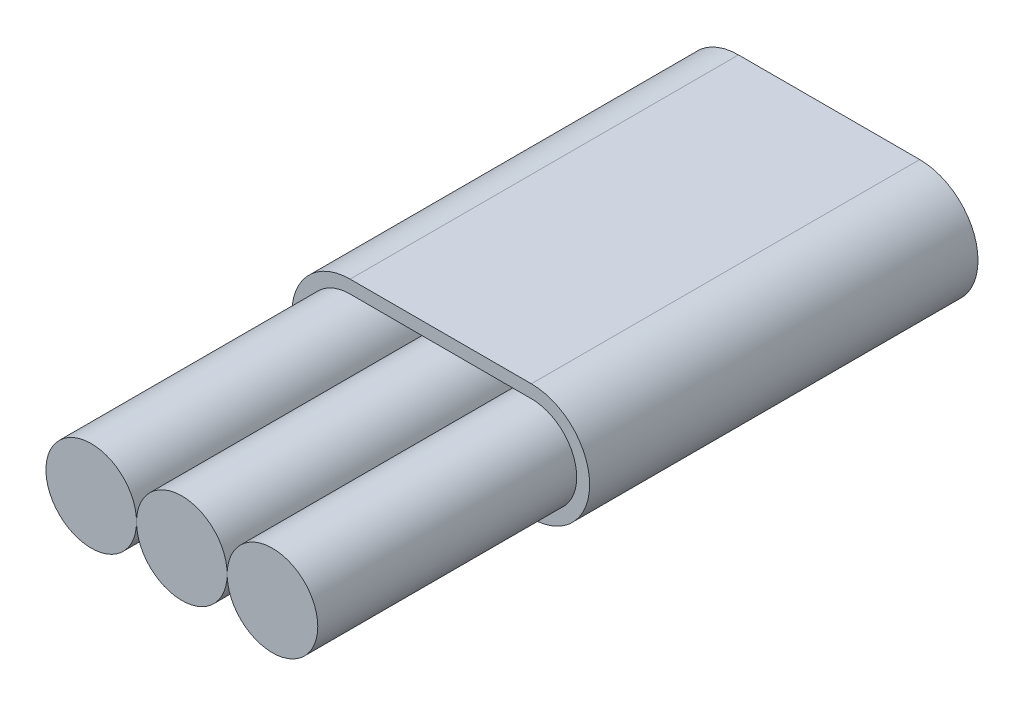
SolidWorks part; units mm, degrees
ref_plane "Front" through (0, 0, 0) normal (0, 0, 1) x (1, 0, 0)
ref_plane "Top" through (0, 0, 0) normal (0, 1, 0) x (1, 0, 0)
ref_plane "Right" through (0, 0, 0) normal (1, 0, 0) x (0, 0, -1)
sketch "Sketch2" plane through (0, 0, 0) normal (0, 0, 1) x (1, 0, 0)
  line L0 (-3.5, 0) -> (0, 0) construction
  line L1 (0, 0) -> (3.5, 0) construction
  circle A0 centre (0, 0) radius 1.75
  circle A1 centre (-3.5, 0) radius 1.75
  circle A2 centre (3.5, 0) radius 1.75
  dimension "D1" = 3.5
  dimension "D2" = 3.5
  dimension "D3" = 3.5
extrude "Boss-Extrude1" add sketch "Sketch2" along normal blind 25 contours A2 | A0 | A1
sketch "Sketch3" plane through (0, 0, 0) normal (0, 0, 1) x (1, 0, 0)
  line L0 (-3.5, 0) -> (3.5, 0) construction
  line L1 (-3.5, 2) -> (3.5, 2)
  line L2 (-3.5, -2) -> (3.5, -2)
  arc A0 (-3.5, 2) -> (-3.5, -2) centre (-3.5, 0) ccw
  arc A1 (3.5, -2) -> (3.5, 2) centre (3.5, 0) ccw
  point P2 (0, 0)
  point P8 (3.9621, 0)
  dimension "D2" = 2
  dimension "D1" = 7
extrude "Extrude-Thin1" add sketch "Sketch3" along normal blind 15 separate body thin thin type mid plane wall 0.5
